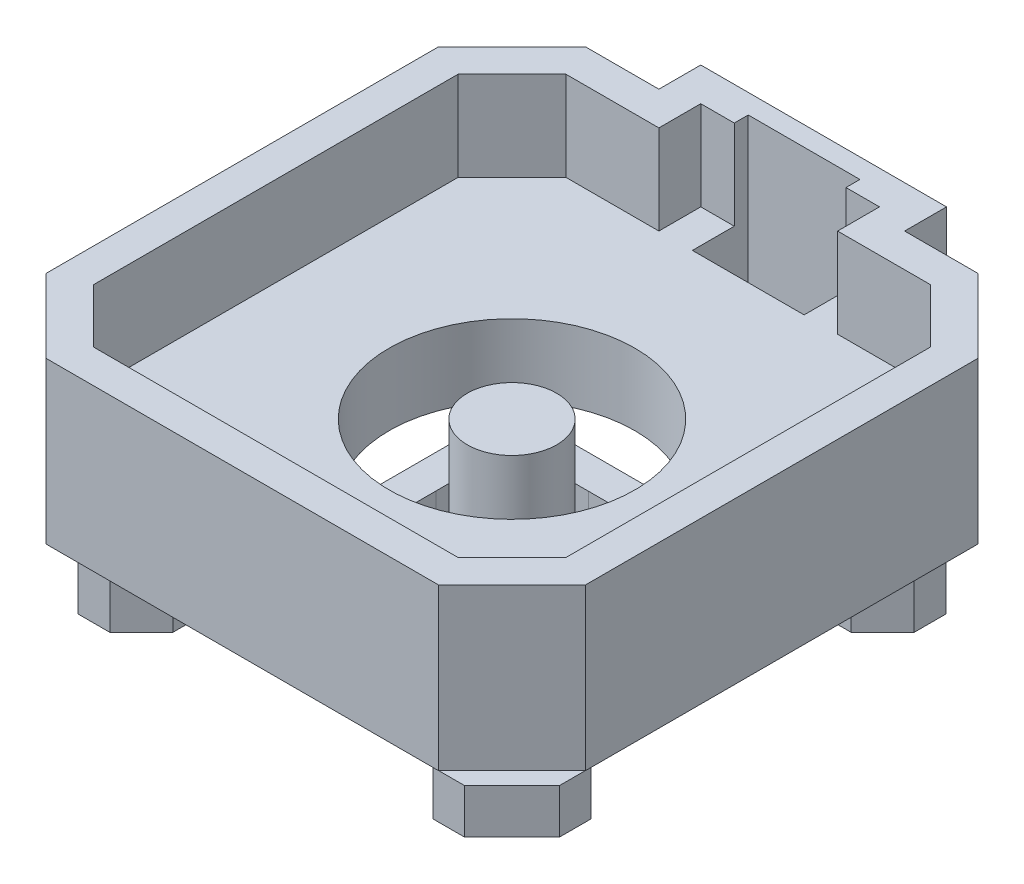
SolidWorks part; units mm, degrees
ref_plane "Front Plane" through (0, 0, 0) normal (0, 0, 1) x (1, 0, 0)
ref_plane "Top Plane" through (0, 0, 0) normal (0, 1, 0) x (1, 0, 0)
ref_plane "Right Plane" through (0, 0, 0) normal (1, 0, 0) x (0, 0, -1)
sketch "Sketch1" plane through (0, 16.3127, 0) normal (0, -1, 0) x (1, 0, 0)
  line L0 (-42.3464, 51.3893) -> (-42.3464, 16.2507)
  line L1 (-42.3464, 16.2507) -> (-35.7657, 9.67)
  line L2 (-35.7657, 9.67) -> (-29.1964, 9.67)
  line L3 (-29.1964, 9.67) -> (-29.1964, 5.92)
  line L4 (-29.1964, 5.92) -> (-7.1964, 5.92)
  line L5 (-7.1964, 5.92) -> (-7.1964, 9.67)
  line L6 (-7.1964, 9.67) -> (-0.6271, 9.67)
  line L7 (-0.6271, 9.67) -> (5.9536, 16.2507)
  line L8 (5.9536, 16.2507) -> (5.9536, 51.3893)
  line L9 (5.9536, 51.3893) -> (-0.6271, 57.97)
  line L10 (-0.6271, 57.97) -> (-35.7657, 57.97)
  line L11 (-35.7657, 57.97) -> (-42.3464, 51.3893)
  line L12 (-10.1964, 12.67) -> (-1.8697, 12.67)
  line L13 (-1.8697, 12.67) -> (2.9536, 17.4933)
  line L14 (2.9536, 17.4933) -> (2.9536, 50.1466)
  line L15 (2.9536, 50.1466) -> (-1.8697, 54.97)
  line L16 (-1.8697, 54.97) -> (-34.5231, 54.97)
  line L17 (-34.5231, 54.97) -> (-39.3464, 50.1466)
  line L18 (-39.3464, 50.1466) -> (-39.3464, 17.4933)
  line L19 (-39.3464, 17.4933) -> (-34.5231, 12.67)
  line L20 (-34.5231, 12.67) -> (-26.1964, 12.67)
  line L21 (-26.1964, 12.67) -> (-26.1964, 8.92)
  line L22 (-26.1964, 8.92) -> (-10.1964, 8.92)
  line L23 (-10.1964, 8.92) -> (-10.1964, 12.67)
  line L24 (-10.1964, 12.67) -> (-1.8697, 12.67)
  line L25 (-1.8697, 12.67) -> (2.9536, 17.4933)
  line L26 (2.9536, 17.4933) -> (2.9536, 50.1466)
  line L27 (2.9536, 50.1466) -> (-1.8697, 54.97)
  line L28 (-1.8697, 54.97) -> (-34.5231, 54.97)
  line L29 (-34.5231, 54.97) -> (-39.3464, 50.1466)
  line L30 (-39.3464, 50.1466) -> (-39.3464, 17.4933)
  line L31 (-39.3464, 17.4933) -> (-34.5231, 12.67)
  line L32 (-34.5231, 12.67) -> (-26.1964, 12.67)
  line L33 (-26.1964, 12.67) -> (-26.1964, 8.92)
  line L34 (-26.1964, 8.92) -> (-10.1964, 8.92)
  line L35 (-10.1964, 8.92) -> (-10.1964, 12.67)
  dimension "D1" = 0
  dimension "D2" = 3
extrude "Boss-Extrude1" add sketch "Sketch1" against normal blind 8
ref_plane "Plane1" through (-35.7657, 16.3127, 57.97) normal (-1, 0, 0) x (0, 0, 1)
sketch "Sketch3" plane through (0, 16.3127, 0) normal (0, -1, 0) x (1, 0, 0)
  line L12 (-35.7657, 57.97) -> (-42.3464, 51.3893)
  line L13 (-42.3464, 51.3893) -> (-42.3464, 16.2507)
  line L14 (-42.3464, 16.2507) -> (-35.7657, 9.67)
  line L15 (-35.7657, 9.67) -> (-29.1964, 9.67)
  line L16 (-29.1964, 9.67) -> (-29.1964, 5.92)
  line L17 (-29.1964, 5.92) -> (-7.1964, 5.92)
  line L18 (-7.1964, 5.92) -> (-7.1964, 9.67)
  line L19 (-7.1964, 9.67) -> (-0.6271, 9.67)
  line L20 (-0.6271, 9.67) -> (5.9536, 16.2507)
  line L21 (5.9536, 16.2507) -> (5.9536, 51.3893)
  line L22 (5.9536, 51.3893) -> (-0.6271, 57.97)
  line L23 (-0.6271, 57.97) -> (-35.7657, 57.97)
  line L24 (-35.7657, 57.97) -> (-42.3464, 51.3893)
  line L25 (-42.3464, 51.3893) -> (-42.3464, 16.2507)
  line L26 (-42.3464, 16.2507) -> (-35.7657, 9.67)
  line L27 (-35.7657, 9.67) -> (-29.1964, 9.67)
  line L28 (-29.1964, 9.67) -> (-29.1964, 5.92)
  line L29 (-29.1964, 5.92) -> (-7.1964, 5.92)
  line L30 (-7.1964, 5.92) -> (-7.1964, 9.67)
  line L31 (-7.1964, 9.67) -> (-0.6271, 9.67)
  line L32 (-0.6271, 9.67) -> (5.9536, 16.2507)
  line L33 (5.9536, 16.2507) -> (5.9536, 51.3893)
  line L34 (5.9536, 51.3893) -> (-0.6271, 57.97)
  line L35 (-0.6271, 57.97) -> (-35.7657, 57.97)
  dimension "D1" = 0
extrude "Boss-Extrude2" add sketch "Sketch3" along normal blind 6.4
sketch "Sketch4" plane through (0, 9.9127, 0) normal (0, -1, 0) x (1, 0, 0)
  line L0 (-39.0561, 54.6796) -> (2.6632, 12.9603) construction
  line L1 (-39.0561, 54.6796) -> (2.6632, 12.9603) construction
  circle A0 centre (-18.1964, 33.82) radius 11 construction
  circle A1 centre (-18.1964, 33.82) radius 11
extrude "Cut-Extrude1" cut sketch "Sketch4" against normal blind 13
sketch "Sketch5" plane through (0, 16.3127, 0) normal (0, -1, 0) x (1, 0, 0)
  circle A0 centre (-18.1964, 33.82) radius 4
extrude "Boss-Extrude3" add sketch "Sketch5" along normal blind 13 separate body
sketch "Sketch6" plane through (0, 3.3127, 0) normal (0, -1, 0) x (1, 0, 0)
  line L0 (-22.0601, 34.8552) -> (-25.0221, 37.8173)
  line L1 (-33.3738, 46.169) -> (-34.0809, 45.4618)
  line L2 (-36.9094, 45.4618) -> (-39.7378, 48.2903)
  line L3 (-39.7378, 51.1187) -> (-35.4951, 55.3613)
  line L4 (-32.6667, 55.3613) -> (-29.8383, 52.5329)
  line L5 (-29.8383, 49.7045) -> (-30.5454, 48.9974)
  line L6 (-30.5454, 48.9974) -> (-25.1964, 43.6484)
  line L7 (-21.0248, 36.6484) -> (-39.0561, 54.6796) construction
  line L8 (-35.4951, 44.0476) -> (-34.0809, 56.7756) construction
  line L9 (-18.1964, 33.82) -> (-18.1964, 57.97) construction
  line L10 (-0.6271, 57.97) -> (-35.7657, 57.97) construction
  line L11 (-25.1964, 43.6484) -> (-18.1964, 43.6484)
  line L12 (-18.1964, 43.6484) -> (-18.1964, 40.6484)
  line L13 (-18.1964, 40.6484) -> (-22.1964, 40.6484)
  line L14 (-22.1964, 40.6484) -> (-19.2317, 37.6837)
  line L15 (-18.1964, 33.82) -> (-42.3464, 33.82) construction
  line L16 (-42.3464, 51.3893) -> (-42.3464, 16.2507) construction
  line L17 (-39.0561, 54.6796) -> (2.6632, 12.9603) construction
  line L18 (-25.1964, 43.6484) -> (-28.0248, 40.82) construction
  line L19 (-22.1964, 40.6484) -> (-25.0221, 37.8173) construction
  line L20 (-28.0248, 40.82) -> (-28.0248, 33.82)
  line L21 (-25.0221, 37.8173) -> (-25.0221, 33.82)
  line L22 (-25.0221, 33.82) -> (-28.0248, 33.82)
  line L23 (-28.0248, 40.82) -> (-33.3738, 46.169)
  line L24 (-35.4951, 55.3613) -> (-32.6667, 55.3613)
  line L25 (-39.7378, 48.2903) -> (-39.7378, 51.1187)
  line L26 (-34.0809, 45.4618) -> (-36.9094, 45.4618)
  line L27 (-29.8383, 52.5329) -> (-29.8383, 49.7045)
  circle A0 centre (-34.788, 50.4116) radius 1.5
  circle A1 centre (-18.1964, 33.82) radius 4 construction
  arc A2 (-19.2317, 37.6837) -> (-22.0601, 34.8552) centre (-18.1964, 33.82) ccw
  arc A3 (-20.0851, 26.1387) -> (-25.8776, 35.7086) centre (-18.1964, 33.82) ccw construction
  point P6 (-41.152, 49.7045)
  point P8 (-28.4241, 51.1187)
  dimension "D5" = 3
  dimension "D9" = 3
  dimension "D1" = 10
  dimension "D2" = 8
  dimension "D3" = 16
  dimension "D4" = 16
  dimension "D6" = 4
  dimension "D7" = 3
  dimension "D8" = 7
extrude "Boss-Extrude4" add sketch "Sketch6" against normal blind 4
pattern_circular "CirPattern2" count 4 over 360 about axis through (-18.1964, 0, 33.82) along (0, 1, 0) of "Boss-Extrude4"
sketch "Sketch7" plane through (0, 24.3127, 0) normal (0, 1, 0) x (1, 0, 0)
  line L0 (-29.1964, -5.92) -> (-7.1964, -5.92) construction
  line L1 (-16.2047, -14.7693) -> (-26.2047, -14.7693)
  line L2 (-16.2047, -14.7693) -> (-16.2047, -5.92)
  line L3 (-16.2047, -5.92) -> (-26.2047, -5.92)
  line L4 (-26.2047, -14.7693) -> (-26.2047, -5.92)
  dimension "D1" = 10
sketch "Sketch8" plane through (0, 24.3127, 0) normal (0, 1, 0) x (1, 0, 0)
  line L7 (-13.1964, -7.67) -> (-13.1964, -12.67)
  line L8 (-13.1964, -12.67) -> (-23.1964, -12.67)
  line L9 (-13.1964, -7.67) -> (-23.1964, -7.67)
  line L10 (-23.1964, -7.67) -> (-23.1964, -12.67)
  line L11 (-34.5231, -12.67) -> (-26.1964, -12.67) construction
  dimension "D2" = 5
extrude "Cut-Extrude2" cut sketch "Sketch8" against normal blind 19
